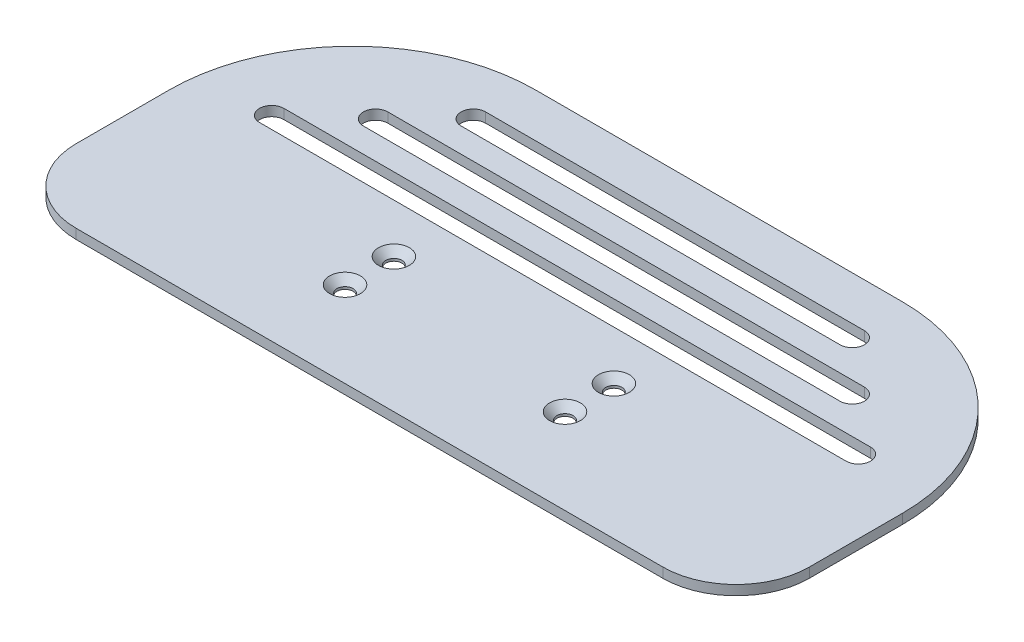
SolidWorks part; units mm, degrees
material "AISI 1020"
ref_plane "Plano frontal" through (0, 0, 0) normal (0, 0, 1) x (1, 0, 0)
ref_plane "Plano superior" through (0, 0, 0) normal (0, 1, 0) x (1, 0, 0)
ref_plane "Plano direito" through (0, 0, 0) normal (1, 0, 0) x (0, 0, -1)
sketch "Esboço2" plane through (0, 0, 0) normal (0, 1, 0) x (1, 0, 0)
  line L1 (75, 71.5) -> (-75, 71.5)
  line L2 (150, -3.5) -> (150, -41.5)
  line L3 (120, -71.5) -> (-120, -71.5)
  line L4 (-150, -3.5) -> (-150, -41.5)
  line L5 (150, 71.5) -> (-150, -71.5) construction
  line L6 (150, -71.5) -> (-150, 71.5) construction
  arc A0 (75, 71.5) -> (150, -3.5) centre (75, -3.5) cw
  arc A1 (-75, 71.5) -> (-150, -3.5) centre (-75, -3.5) ccw
  arc A2 (150, -41.5) -> (120, -71.5) centre (120, -41.5) cw
  arc A3 (-120, -71.5) -> (-150, -41.5) centre (-120, -41.5) cw
  point P0 (0, 0)
  dimension "D3" = 75
  dimension "D4" = 30
  dimension "D1" = 143
  dimension "D2" = 300
extrude "Ressalto-extrusão1" add sketch "Esboço2" along normal mid plane 4
sketch "Esboço3" plane through (0, 2, 0) normal (0, 1, 0) x (1, 0, 0)
  line L0 (-77.5, 48.5) -> (77.5, 48.5) construction
  line L1 (-77.5, 53.5) -> (77.5, 53.5)
  line L2 (-77.5, 43.5) -> (77.5, 43.5)
  line L3 (-97.5, 28.5) -> (97.5, 28.5) construction
  line L4 (-97.5, 33.5) -> (97.5, 33.5)
  line L5 (-97.5, 23.5) -> (97.5, 23.5)
  line L6 (-120, 8.5) -> (120, 8.5) construction
  line L7 (-120, 13.5) -> (120, 13.5)
  line L8 (-120, 3.5) -> (120, 3.5)
  line L9 (75, 71.5) -> (-75, 71.5) construction
  arc A0 (-77.5, 53.5) -> (-77.5, 43.5) centre (-77.5, 48.5) ccw
  arc A1 (77.5, 43.5) -> (77.5, 53.5) centre (77.5, 48.5) ccw
  arc A2 (-97.5, 33.5) -> (-97.5, 23.5) centre (-97.5, 28.5) ccw
  arc A3 (97.5, 23.5) -> (97.5, 33.5) centre (97.5, 28.5) ccw
  arc A4 (-120, 13.5) -> (-120, 3.5) centre (-120, 8.5) ccw
  arc A5 (120, 3.5) -> (120, 13.5) centre (120, 8.5) ccw
  point P2 (0, 48.5)
  point P7 (0, 28.5)
  point P14 (0, 8.5)
  dimension "D1" = 5
  dimension "D2" = 5
  dimension "D3" = 5
  dimension "D4" = 155
  dimension "D5" = 195
  dimension "D6" = 240
  dimension "D7" = 18
  dimension "D8" = 10
  dimension "D9" = 10
extrude "Corte-extrusão1" cut sketch "Esboço3" against normal through all
hole_wizard "Escareado para parafuso com cabeça escareada elevada de M61" positions "Esboço4" profile "Esboço5" countersink size "M6" standard "DIN" end condition through all
sketch "Esboço4" plane through (0, 2, 0) normal (0, 1, 0) x (1, 0, 0)
  line L0 (-120, -71.5) -> (120, -71.5) construction
  point P0 (-45, -36.5)
  dimension "D1" = 35
  dimension "D2" = 45
sketch "Esboço5" plane through (-45, 2, 36.5) normal (1, 0, 0) x (0, 0, 1)
  line L0 (0, 0) -> (0, 4)
  line L1 (0, 4) -> (3.3, 4)
  line L2 (3.3, 4) -> (3.3, 3)
  line L3 (3.3, 3) -> (6.3, 0)
  line L5 (6.3, 0) -> (0, 0)
  line L6 (-3.3, 3) -> (-6.3, 0) construction
  line L11 (0, -6.35) -> (0, 107.95) construction
  dimension "Thru Hole Dia." = 6.6
  dimension "Thru Hole Depth" = 4
  dimension "Near C'Sink Dia." = 12.6
  dimension "Near C'Sink Angle" = 90
pattern_linear "Padrão linear1" count 2 spacing 90 along (1, 0, 0) count 2 spacing 20 along (0, 0, -1) of "Escareado para parafuso com cabeça escareada elevada de M61"
